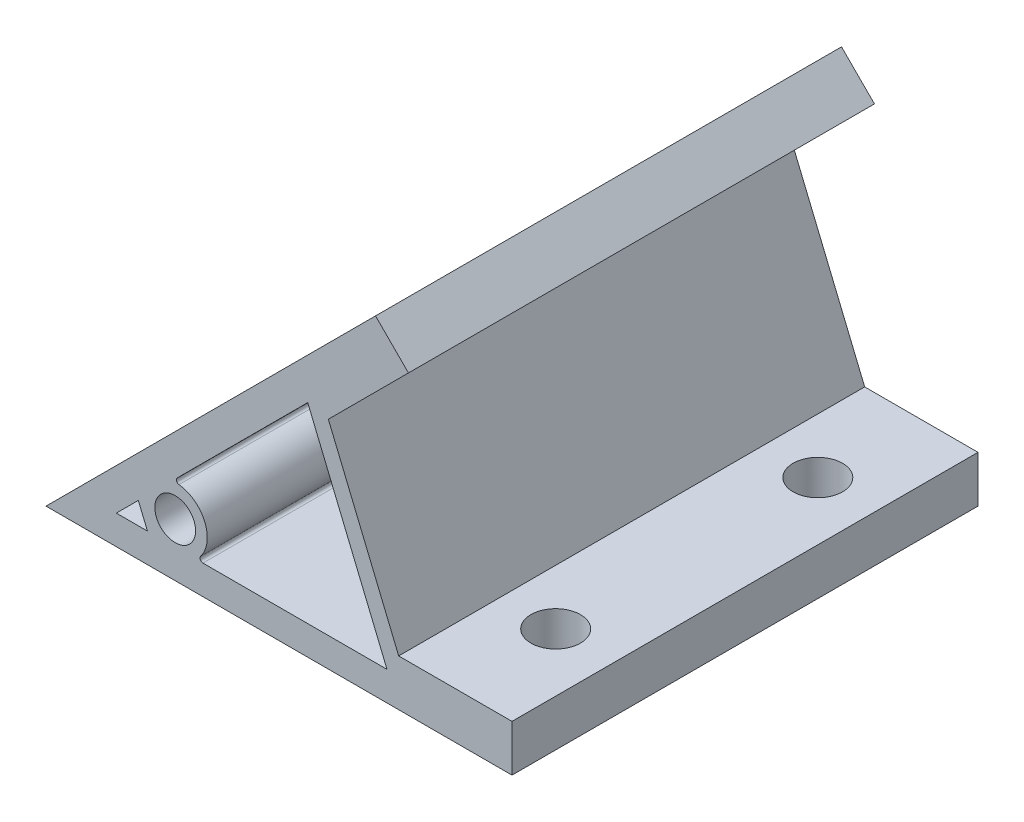
SolidWorks part; units mm, degrees
ref_plane "前视基准面" through (0, 0, 0) normal (0, 0, 1) x (1, 0, 0)
ref_plane "上视基准面" through (0, 0, 0) normal (0, 1, 0) x (1, 0, 0)
ref_plane "右视基准面" through (0, 0, 0) normal (1, 0, 0) x (0, 0, -1)
sketch "草图1" plane through (0, 0, 0) normal (0, 0, 1) x (1, 0, 0)
  line L0 (0, 0) -> (56.5685, 56.5685)
  line L1 (0, 0) -> (80, 0)
  line L2 (12.0711, 5) -> (15.8477, 8.7766)
  line L3 (12.0711, 5) -> (17.412, 5)
  line L4 (15.8477, 8.7766) -> (17.412, 5)
  line L5 (0, 0) -> (16.6385, 6.8674) construction
  line L6 (22.5392, 15.4681) -> (44.9316, 37.8605)
  line L7 (26.9418, 5) -> (58.5429, 5)
  line L8 (12.0711, 5) -> (60.1041, 53.033) construction
  line L9 (58.5429, 5) -> (44.9316, 37.8605)
  line L10 (12.0711, 5) -> (80, 5) construction
  line L11 (60.5474, 8) -> (48.4704, 37.1566)
  line L12 (61.3145, 6.1481) -> (47.7033, 39.0086) construction
  line L13 (62.2254, 50.9117) -> (56.5685, 56.5685)
  line L14 (80, 0) -> (80, 8)
  line L15 (60.5474, 8) -> (80, 8)
  line L16 (50.7665, 39.4527) -> (62.2254, 50.9117) construction
  line L17 (48.4704, 37.1566) -> (62.2254, 50.9117)
  line L18 (63.7946, 8) -> (50.7665, 39.4527) construction
  line L19 (63.7946, 8) -> (80, 8) construction
  line L20 (61.7901, 5) -> (80, 5) construction
  line L21 (47.2277, 40.1566) -> (60.1041, 53.033) construction
  line L23 (61.7901, 5) -> (47.2277, 40.1566) construction
  circle A0 centre (22.1847, 9.1565) radius 3.5
  arc A1 (26.5454, 5.8047) -> (22.8337, 14.618) centre (22.1847, 9.1565) ccw
  arc A2 (26.9418, 5) -> (26.5454, 5.8047) centre (26.9418, 5.5) cw
  circle A3 centre (22.1847, 9.1565) radius 5.5 construction
  arc A4 (22.5392, 15.4681) -> (22.8337, 14.618) centre (22.8927, 15.1145) ccw
  point P15 (27.6847, 9.1565)
  point P20 (25.7866, 5)
  point P23 (21.7067, 14.6357)
  dimension "D7" = 7
  dimension "D8" = 2
  dimension "D9" = 0.5
  dimension "D10" = 56
  dimension "D1" = 45
  dimension "D2" = 80
  dimension "D4" = 67.5
  dimension "D5" = 18
  dimension "D6" = 6
  dimension "D3" = 5
  dimension "D11" = 3
  dimension "D12" = 3
extrude "凸台-拉伸1" add sketch "草图1" along normal mid plane 80
sketch "草图2" plane through (0, 0, 0) normal (-0.7071, 0.7071, 0) x (0, 0, 1)
  line L0 (40, 80) -> (40, 0) construction
  line L1 (40, 80) -> (-40, 80) construction
  line L2 (0, 80) -> (0, 60.6108) construction
  circle A0 centre (22.5, 70) radius 4.25
  circle A1 centre (-22.5, 70) radius 4.25
  dimension "D1" = 10
  dimension "D3" = 8.5
  dimension "D2" = 17.5
extrude "切除-拉伸1" cut sketch "草图2" against normal blind 20
sketch "草图3" plane through (0, 0, 0) normal (0, -1, 0) x (1, 0, 0)
  line L0 (0, 40) -> (80, 40) construction
  line L1 (80, 40) -> (80, -40) construction
  line L2 (80, 0) -> (95.7601, 0) construction
  circle A0 centre (70, 22.5) radius 4.25
  circle A1 centre (70, -22.5) radius 4.25
  dimension "D1" = 17.5
  dimension "D2" = 10
  dimension "D3" = 8.5
extrude "切除-拉伸2" cut sketch "草图3" against normal blind 20
